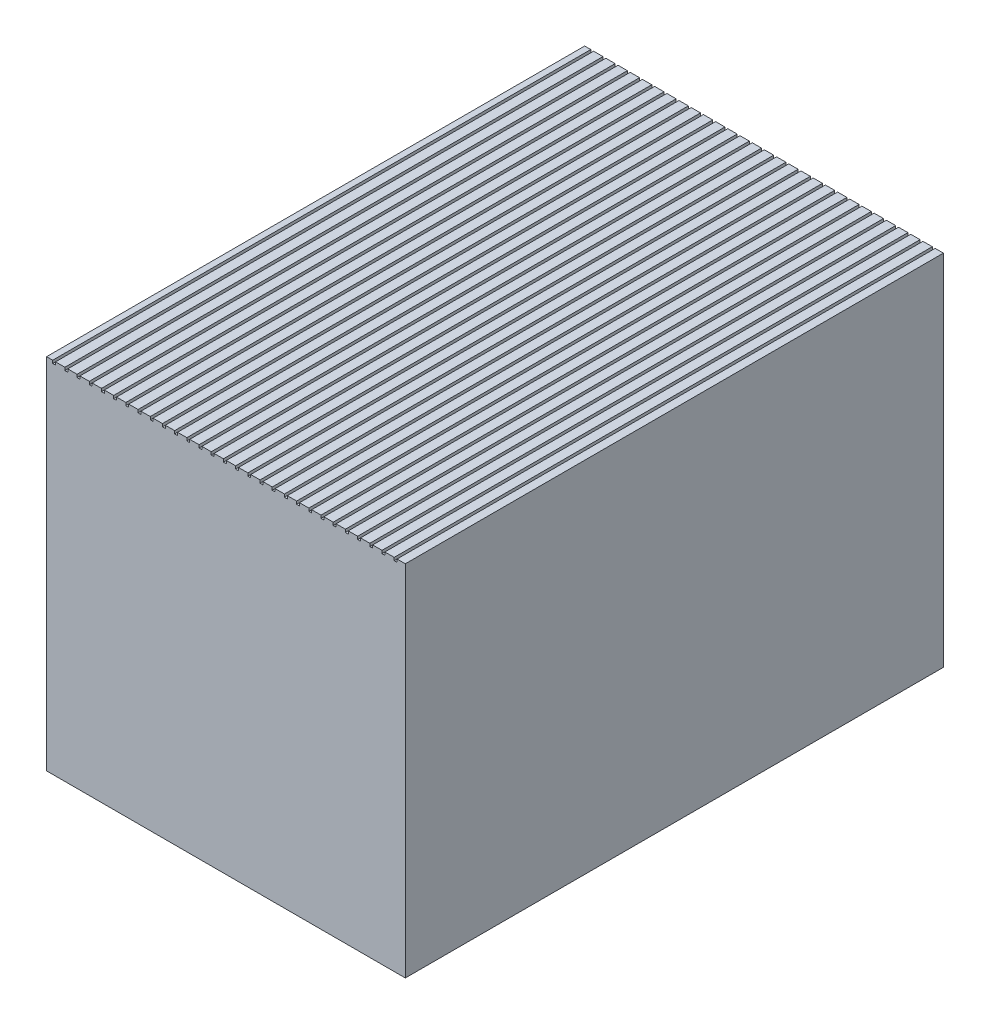
SolidWorks part; units mm, degrees
ref_plane "前视基准面" through (0, 0, 0) normal (0, 0, 1) x (1, 0, 0)
ref_plane "上视基准面" through (0, 0, 0) normal (0, 1, 0) x (1, 0, 0)
ref_plane "右视基准面" through (0, 0, 0) normal (1, 0, 0) x (0, 0, -1)
sketch "草图2" plane through (0, 0, 0) normal (0, 1, 0) x (1, 0, 0)
  line L1 (500, -750) -> (-500, -750)
  line L2 (500, -750) -> (500, 750)
  line L3 (500, 750) -> (-500, 750)
  line L4 (-500, -750) -> (-500, 750)
  line L5 (500, -750) -> (-500, 750) construction
  line L6 (500, 750) -> (-500, -750) construction
  point P0 (0, 0)
  dimension "D1" = 1500
  dimension "D2" = 1000
extrude "凸台-拉伸1" add sketch "草图2" along normal blind 1000
sketch "草图4" plane through (0, 0, 750) normal (0, 0, 1) x (1, 0, 0)
  line L0 (-500, 1000) -> (500, 1000) construction
  line L1 (-483, 1000) -> (-475, 1000)
  line L2 (-483, 1000) -> (-483, 992)
  line L3 (-483, 992) -> (-475, 992)
  line L4 (-475, 1000) -> (-475, 992)
  line L6 (-449, 1000) -> (-449, 992)
  line L7 (-449, 1000) -> (-441, 1000)
  line L8 (-441, 1000) -> (-441, 992)
  line L9 (-449, 992) -> (-441, 992)
  line L10 (-415, 1000) -> (-415, 992)
  line L11 (-415, 1000) -> (-407, 1000)
  line L12 (-407, 1000) -> (-407, 992)
  line L13 (-415, 992) -> (-407, 992)
  line L14 (-381, 1000) -> (-381, 992)
  line L15 (-381, 1000) -> (-373, 1000)
  line L16 (-373, 1000) -> (-373, 992)
  line L17 (-381, 992) -> (-373, 992)
  line L18 (-347, 1000) -> (-347, 992)
  line L19 (-347, 1000) -> (-339, 1000)
  line L20 (-339, 1000) -> (-339, 992)
  line L21 (-347, 992) -> (-339, 992)
  line L22 (-313, 1000) -> (-313, 992)
  line L23 (-313, 1000) -> (-305, 1000)
  line L24 (-305, 1000) -> (-305, 992)
  line L25 (-313, 992) -> (-305, 992)
  line L26 (-279, 1000) -> (-279, 992)
  line L27 (-279, 1000) -> (-271, 1000)
  line L28 (-271, 1000) -> (-271, 992)
  line L29 (-279, 992) -> (-271, 992)
  line L30 (-245, 1000) -> (-245, 992)
  line L31 (-245, 1000) -> (-237, 1000)
  line L32 (-237, 1000) -> (-237, 992)
  line L33 (-245, 992) -> (-237, 992)
  line L34 (-211, 1000) -> (-211, 992)
  line L35 (-211, 1000) -> (-203, 1000)
  line L36 (-203, 1000) -> (-203, 992)
  line L37 (-211, 992) -> (-203, 992)
  line L38 (-177, 1000) -> (-177, 992)
  line L39 (-177, 1000) -> (-169, 1000)
  line L40 (-169, 1000) -> (-169, 992)
  line L41 (-177, 992) -> (-169, 992)
  line L42 (-143, 1000) -> (-143, 992)
  line L43 (-143, 1000) -> (-135, 1000)
  line L44 (-135, 1000) -> (-135, 992)
  line L45 (-143, 992) -> (-135, 992)
  line L46 (-109, 1000) -> (-109, 992)
  line L47 (-109, 1000) -> (-101, 1000)
  line L48 (-101, 1000) -> (-101, 992)
  line L49 (-109, 992) -> (-101, 992)
  line L50 (-75, 1000) -> (-75, 992)
  line L51 (-75, 1000) -> (-67, 1000)
  line L52 (-67, 1000) -> (-67, 992)
  line L53 (-75, 992) -> (-67, 992)
  line L54 (-41, 1000) -> (-41, 992)
  line L55 (-41, 1000) -> (-33, 1000)
  line L56 (-33, 1000) -> (-33, 992)
  line L57 (-41, 992) -> (-33, 992)
  line L58 (-7, 1000) -> (-7, 992)
  line L59 (-7, 1000) -> (1, 1000)
  line L60 (1, 1000) -> (1, 992)
  line L61 (-7, 992) -> (1, 992)
  line L62 (27, 1000) -> (27, 992)
  line L63 (27, 1000) -> (35, 1000)
  line L64 (35, 1000) -> (35, 992)
  line L65 (27, 992) -> (35, 992)
  line L66 (61, 1000) -> (61, 992)
  line L67 (61, 1000) -> (69, 1000)
  line L68 (69, 1000) -> (69, 992)
  line L69 (61, 992) -> (69, 992)
  line L70 (95, 1000) -> (95, 992)
  line L71 (95, 1000) -> (103, 1000)
  line L72 (103, 1000) -> (103, 992)
  line L73 (95, 992) -> (103, 992)
  line L74 (129, 1000) -> (129, 992)
  line L75 (129, 1000) -> (137, 1000)
  line L76 (137, 1000) -> (137, 992)
  line L77 (129, 992) -> (137, 992)
  line L78 (163, 1000) -> (163, 992)
  line L79 (163, 1000) -> (171, 1000)
  line L80 (171, 1000) -> (171, 992)
  line L81 (163, 992) -> (171, 992)
  line L82 (197, 1000) -> (197, 992)
  line L83 (197, 1000) -> (205, 1000)
  line L84 (205, 1000) -> (205, 992)
  line L85 (197, 992) -> (205, 992)
  line L86 (231, 1000) -> (231, 992)
  line L87 (231, 1000) -> (239, 1000)
  line L88 (239, 1000) -> (239, 992)
  line L89 (231, 992) -> (239, 992)
  line L90 (265, 1000) -> (265, 992)
  line L91 (265, 1000) -> (273, 1000)
  line L92 (273, 1000) -> (273, 992)
  line L93 (265, 992) -> (273, 992)
  line L94 (299, 1000) -> (299, 992)
  line L95 (299, 1000) -> (307, 1000)
  line L96 (307, 1000) -> (307, 992)
  line L97 (299, 992) -> (307, 992)
  line L98 (333, 1000) -> (333, 992)
  line L99 (333, 1000) -> (341, 1000)
  line L100 (341, 1000) -> (341, 992)
  line L101 (333, 992) -> (341, 992)
  line L102 (367, 1000) -> (367, 992)
  line L103 (367, 1000) -> (375, 1000)
  line L104 (375, 1000) -> (375, 992)
  line L105 (367, 992) -> (375, 992)
  line L106 (401, 1000) -> (401, 992)
  line L107 (401, 1000) -> (409, 1000)
  line L108 (409, 1000) -> (409, 992)
  line L109 (401, 992) -> (409, 992)
  line L110 (435, 1000) -> (435, 992)
  line L111 (435, 1000) -> (443, 1000)
  line L112 (443, 1000) -> (443, 992)
  line L113 (435, 992) -> (443, 992)
  line L114 (469, 1000) -> (469, 992)
  line L115 (469, 1000) -> (477, 1000)
  line L116 (477, 1000) -> (477, 992)
  line L117 (469, 992) -> (477, 992)
  line L122 (-500, 1000) -> (-500, 0) construction
  dimension "D1" = 8
  dimension "D2" = 17
  dimension "D3" = 8
  dimension "D4" = 29
  dimension "D5" = 8
  dimension "D6" = 90
extrude "切除-拉伸1" cut sketch "草图4" against normal blind 1500
ref_plane "基准面1" through (-483, 992, 750) normal (1, 0, 0) x (0, 0, -1)
